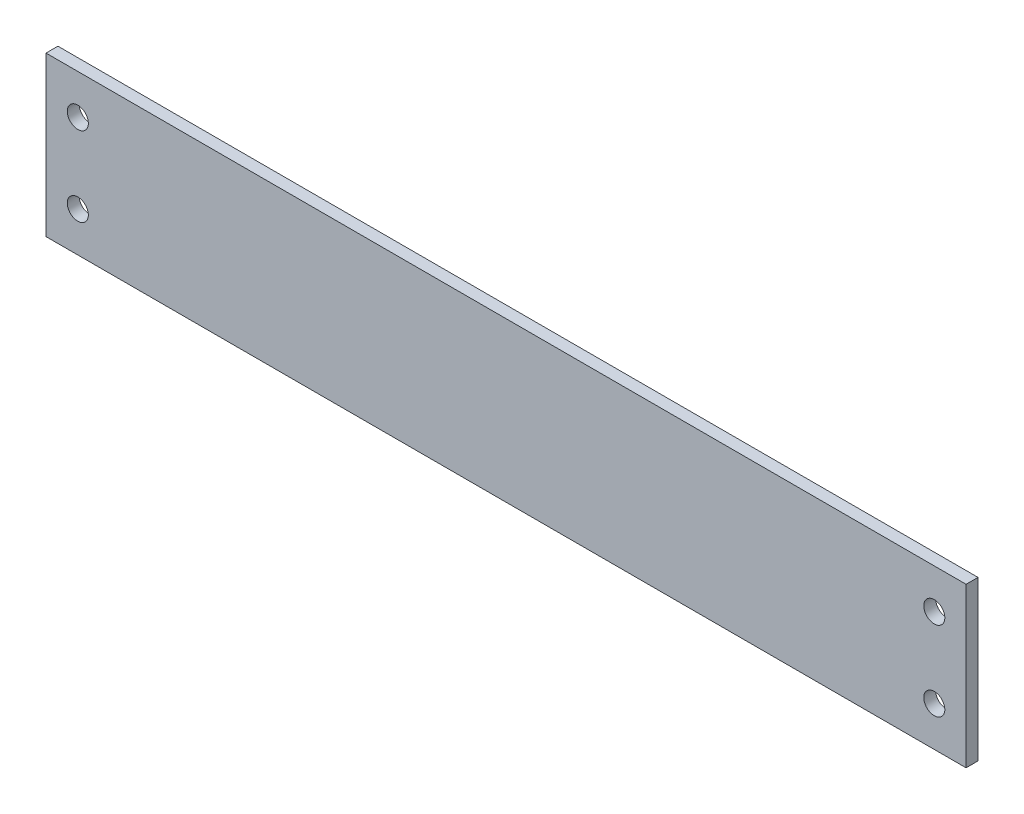
SolidWorks part; units mm, degrees
ref_plane "Front Plane" through (0, 0, 0) normal (0, 0, 1) x (1, 0, 0)
ref_plane "Top Plane" through (0, 0, 0) normal (0, 1, 0) x (1, 0, 0)
ref_plane "Right Plane" through (0, 0, 0) normal (1, 0, 0) x (0, 0, -1)
sketch "Extrusion Base Sketch" plane through (0, 0, 0) normal (0, 0, 1) x (1, 0, 0)
  line L0 (209.5, 36.75) -> (209.5, -3.25)
  line L1 (0, 0) -> (187.5, 0) construction
  line L2 (0, 0) -> (0, 33.5) construction
  line L3 (0, 33.5) -> (187.5, 33.5) construction
  line L4 (187.5, 0) -> (187.5, 33.5) construction
  line L5 (-22, 36.75) -> (209.5, 36.75)
  line L6 (-3.25, 36.75) -> (-3.25, -3.25) construction
  line L7 (-22, -3.25) -> (209.5, -3.25)
  line L8 (190.75, 36.75) -> (190.75, -3.25) construction
  line L9 (-22, 36.75) -> (-22, -3.25)
  line L10 (201.5, 26.75) -> (201.5, 6.75) construction
  line L11 (201.5, 16.75) -> (209.5, 16.75) construction
  circle A0 centre (-14, 26.75) radius 2.65
  circle A1 centre (-14, 6.75) radius 2.65
  circle A2 centre (201.5, 26.75) radius 2.65
  circle A3 centre (201.5, 6.75) radius 2.65
  dimension "D8" = 5.3
  dimension "D1" = 33.5
  dimension "D2" = 187.5
  dimension "D4" = 3.25
  dimension "D5" = 3.25
  dimension "D6" = 3.25
  dimension "D7" = 20
  dimension "D3" = 40
extrude "Extrusion Base Extrude" add sketch "Extrusion Base Sketch" against normal blind 3
equation "\"Logo Height\"= 33.5mm"
equation "\"Total Height\"= 40mm"
equation "\"Border\"= ( \"Total Height\" - \"Logo Height\" ) / 2"
equation "\"Logo Length\"= 187.5mm"
equation "\"D1@Extrusion Base Sketch\" = \"Logo Height\""
equation "\"D2@Extrusion Base Sketch\" = \"Logo Length\""
equation "\"D4@Extrusion Base Sketch\" = \"Border\""
equation "\"D5@Extrusion Base Sketch\" = \"Border\""
equation "\"D6@Extrusion Base Sketch\" = \"Border\""
equation "\"D3@Extrusion Base Sketch\" = \"Total Height\""
